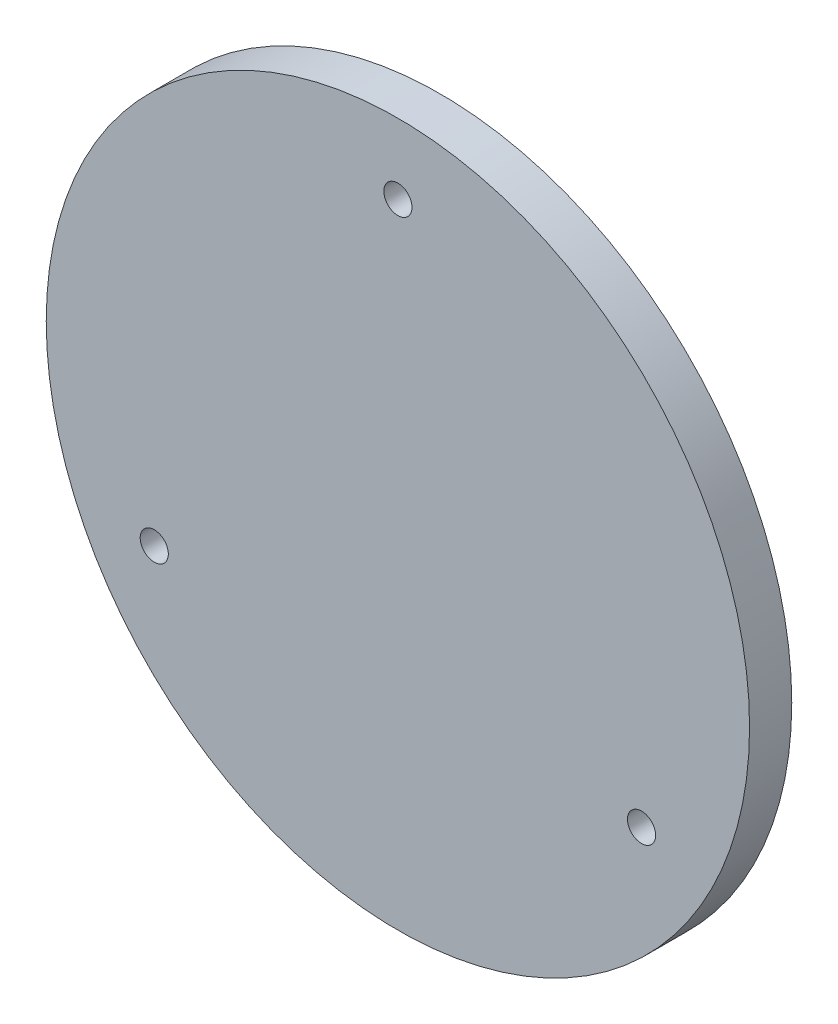
SolidWorks part; units mm, degrees
material "ABS PC"
ref_plane "前视基准面" through (0, 0, 0) normal (0, 0, 1) x (1, 0, 0)
ref_plane "上视基准面" through (0, 0, 0) normal (0, 1, 0) x (1, 0, 0)
ref_plane "右视基准面" through (0, 0, 0) normal (1, 0, 0) x (0, 0, -1)
sketch "草图1" plane through (0, 0, 0) normal (0, 0, 1) x (1, 0, 0)
  line L0 (0, 0) -> (0, 25) construction
  line L1 (0, 0) -> (-21.6506, -12.5) construction
  line L2 (0, 0) -> (21.6506, -12.5) construction
  circle A6 centre (0, 0) radius 25
  circle A7 centre (0, 20) radius 1
  circle A8 centre (-17.3205, -10) radius 1
  circle A9 centre (17.3205, -10) radius 1
  dimension "D1" = 50
  dimension "D2" = 120
  dimension "D7" = 2
  dimension "D8" = 2
  dimension "D9" = 2
  dimension "D3" = 120
  dimension "D4" = 20
  dimension "D5" = 20
  dimension "D6" = 20
extrude "凸台-拉伸1" add sketch "草图1" along normal blind 3
